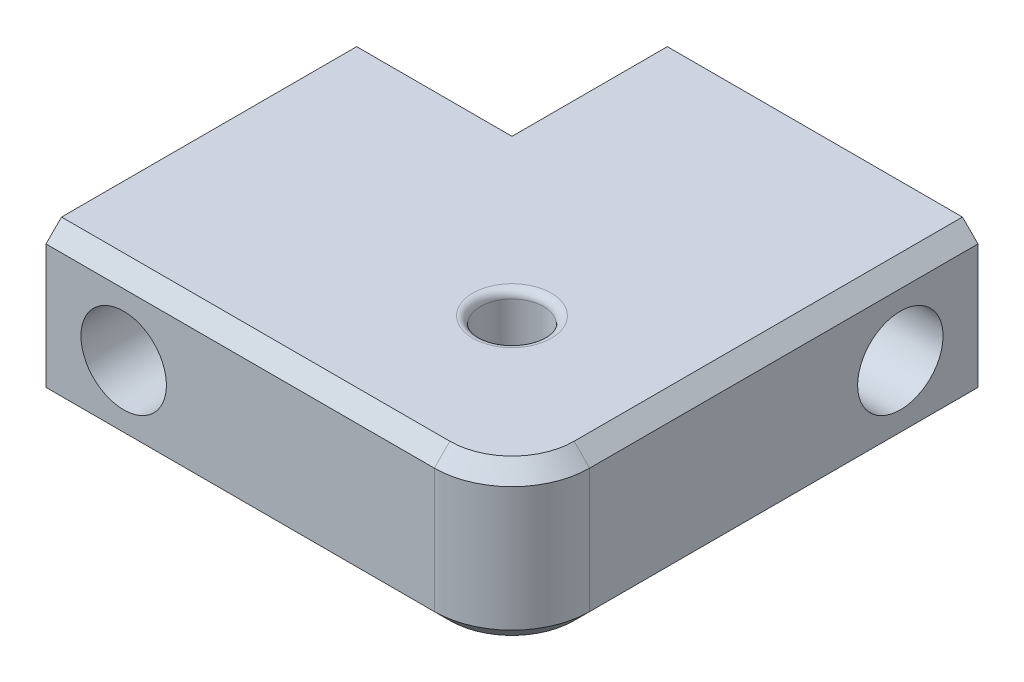
SolidWorks part; units mm, degrees
ref_plane "Front Plane" through (0, 0, 0) normal (0, 0, 1) x (1, 0, 0)
ref_plane "Top Plane" through (0, 0, 0) normal (0, 1, 0) x (1, 0, 0)
ref_plane "Right Plane" through (0, 0, 0) normal (1, 0, 0) x (0, 0, -1)
sketch "Sketch1" plane through (0, 0, 0) normal (0, 1, 0) x (1, 0, 0)
  line L0 (-20, 40) -> (20, 40)
  line L5 (20, -20) -> (-20, 20) construction
  line L6 (20, 20) -> (-20, -20) construction
  line L11 (20, 40) -> (20, -10)
  line L12 (10, -20) -> (-40, -20)
  line L13 (-40, -20) -> (-40, 20)
  line L14 (-20, 20) -> (-40, 20)
  line L15 (-20, 20) -> (-20, 40)
  arc A0 (10, -20) -> (20, -10) centre (10, -10) ccw
  circle A1 centre (0, 0) radius 4.05
  point P0 (0, 0)
  dimension "D3" = 10
  dimension "D4" = 8.1
  dimension "D1" = 40
  dimension "D2" = 40
extrude "Boss-Extrude1" add sketch "Sketch1" along normal blind 20
fillet "Fillet1" radius 1 1 edges at (0, 20, 4.05)
chamfer "Chamfer2" distance 2 angle 45 6 edges at (20, 0, -15) (17.0711, 0, 17.0711) (-15, 0, 20) (20, 20, -15) (17.0711, 20, 17.0711) (-15, 20, 20)
sketch "Sketch7" plane through (-20, 0, 0) normal (-1, 0, 0) x (0, 0, 1)
  circle A0 centre (-30, 10) radius 2.65
  dimension "D1" = 5.3
extrude "Cut-Extrude8" cut sketch "Sketch7" against normal blind 40
sketch "Sketch8" plane through (0, 0, -20) normal (0, 0, -1) x (-1, 0, 0)
  circle A0 centre (30, 10) radius 2.65
  dimension "D1" = 5.3
extrude "Cut-Extrude9" cut sketch "Sketch8" against normal blind 40
ref_plane "Plane1" through (-9, 0, 0) normal (-1, 0, 0) x (0, 0, 1)
ref_plane "Plane2" through (0, 0, -9) normal (0, 0, -1) x (-1, 0, 0)
sketch "Sketch9" plane through (-9, 0, 0) normal (-1, 0, 0) x (0, 0, 1)
  circle A0 centre (-30, 10) radius 5.5
  dimension "D1" = 11
extrude "Cut-Extrude10" cut sketch "Sketch9" against normal blind 40
sketch "Sketch10" plane through (0, 0, -9) normal (0, 0, -1) x (-1, 0, 0)
  circle A0 centre (30, 10) radius 5.5
  dimension "D1" = 11
extrude "Cut-Extrude11" cut sketch "Sketch10" against normal blind 40
